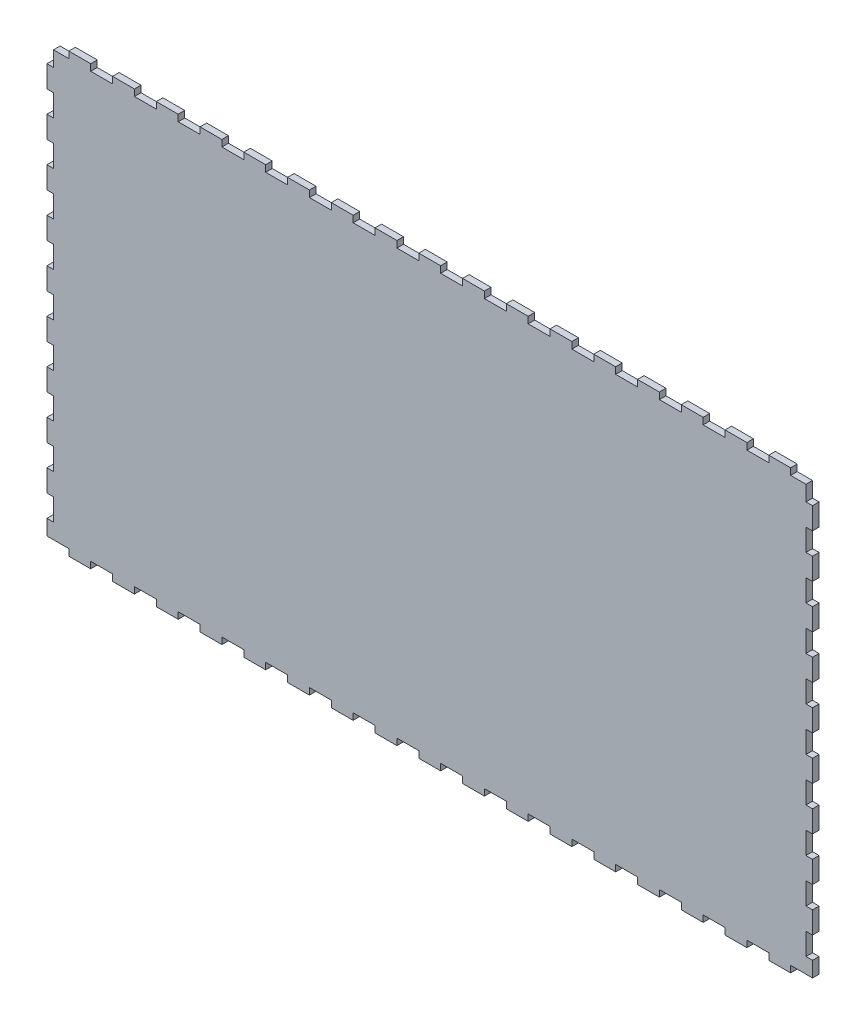
SolidWorks part; units mm, degrees
ref_plane "Alzado" through (0, 0, 0) normal (0, 0, 1) x (1, 0, 0)
ref_plane "Planta" through (0, 0, 0) normal (0, 1, 0) x (1, 0, 0)
ref_plane "Vista lateral" through (0, 0, 0) normal (1, 0, 0) x (0, 0, -1)
sketch "Croquis1" plane through (0, 0, 0) normal (0, 0, 1) x (1, 0, 0)
  line L0 (-175, -97) -> (-165, -97)
  line L1 (-155, -97) -> (-145, -97)
  line L2 (-175, 80) -> (-172, 80)
  line L3 (-172, 70) -> (-175, 70)
  line L4 (175, -100) -> (-175, 100) construction
  line L5 (175, 100) -> (-175, -100) construction
  line L102 (172, 97) -> (172, 90)
  line L103 (-172, 90) -> (-175, 90)
  line L104 (-175, 90) -> (-175, 80)
  line L105 (-175, 80) -> (-172, 80)
  line L106 (-175, 70) -> (-175, 60)
  line L107 (-175, 60) -> (-172, 60)
  line L108 (-172, 80) -> (-172, 70)
  line L109 (-175, 60) -> (-172, 60)
  line L110 (-172, 50) -> (-175, 50)
  line L111 (-175, 50) -> (-175, 40)
  line L112 (-175, 40) -> (-172, 40)
  line L113 (-172, 60) -> (-172, 50)
  line L114 (-175, 40) -> (-172, 40)
  line L115 (-172, 30) -> (-175, 30)
  line L116 (-175, 30) -> (-175, 20)
  line L117 (-175, 20) -> (-172, 20)
  line L118 (-172, 40) -> (-172, 30)
  line L119 (-175, 20) -> (-172, 20)
  line L120 (-172, 10) -> (-175, 10)
  line L121 (-175, 10) -> (-175, 0)
  line L122 (-175, 0) -> (-172, 0)
  line L123 (-172, 20) -> (-172, 10)
  line L124 (-175, 0) -> (-172, 0)
  line L125 (-172, -10) -> (-175, -10)
  line L126 (-175, -10) -> (-175, -20)
  line L127 (-175, -20) -> (-172, -20)
  line L128 (-172, 0) -> (-172, -10)
  line L129 (-175, -20) -> (-172, -20)
  line L130 (-172, -30) -> (-175, -30)
  line L131 (-175, -30) -> (-175, -40)
  line L132 (-175, -40) -> (-172, -40)
  line L133 (-172, -20) -> (-172, -30)
  line L134 (-175, -40) -> (-172, -40)
  line L135 (-172, -50) -> (-175, -50)
  line L136 (-175, -50) -> (-175, -60)
  line L137 (-175, -60) -> (-172, -60)
  line L138 (-172, -40) -> (-172, -50)
  line L139 (-175, -60) -> (-172, -60)
  line L140 (-172, -70) -> (-175, -70)
  line L141 (-175, -70) -> (-175, -80)
  line L142 (-175, -80) -> (-172, -80)
  line L143 (-172, -60) -> (-172, -70)
  line L144 (-175, -80) -> (-172, -80)
  line L145 (-172, -90) -> (-175, -90)
  line L146 (-175, -90) -> (-175, -97)
  line L147 (-145, -97) -> (-145, -100)
  line L148 (-172, -80) -> (-172, -90)
  line L149 (-33.9734, 0) -> (38.9566, 0) construction
  line L150 (172, -80) -> (172, -90)
  line L151 (165, 97) -> (172, 97)
  line L152 (175, -90) -> (175, -97)
  line L153 (172, -90) -> (175, -90)
  line L154 (175, -80) -> (172, -80)
  line L155 (172, -60) -> (172, -70)
  line L156 (175, -80) -> (172, -80)
  line L157 (175, -70) -> (175, -80)
  line L158 (172, -70) -> (175, -70)
  line L159 (175, -60) -> (172, -60)
  line L160 (172, -40) -> (172, -50)
  line L161 (175, -60) -> (172, -60)
  line L162 (175, -50) -> (175, -60)
  line L163 (172, -50) -> (175, -50)
  line L164 (175, -40) -> (172, -40)
  line L165 (172, -20) -> (172, -30)
  line L166 (175, -40) -> (172, -40)
  line L167 (175, -30) -> (175, -40)
  line L168 (172, -30) -> (175, -30)
  line L169 (175, -20) -> (172, -20)
  line L170 (172, 0) -> (172, -10)
  line L171 (175, -20) -> (172, -20)
  line L172 (175, -10) -> (175, -20)
  line L173 (172, -10) -> (175, -10)
  line L174 (175, 0) -> (172, 0)
  line L175 (172, 20) -> (172, 10)
  line L176 (175, 0) -> (172, 0)
  line L177 (175, 10) -> (175, 0)
  line L178 (172, 10) -> (175, 10)
  line L179 (175, 20) -> (172, 20)
  line L180 (172, 40) -> (172, 30)
  line L181 (175, 20) -> (172, 20)
  line L182 (175, 30) -> (175, 20)
  line L183 (172, 30) -> (175, 30)
  line L184 (175, 40) -> (172, 40)
  line L185 (172, 60) -> (172, 50)
  line L186 (175, 40) -> (172, 40)
  line L187 (175, 50) -> (175, 40)
  line L188 (172, 50) -> (175, 50)
  line L189 (175, 60) -> (172, 60)
  line L190 (172, 80) -> (172, 70)
  line L191 (175, 60) -> (172, 60)
  line L192 (175, 70) -> (175, 60)
  line L193 (175, 80) -> (172, 80)
  line L194 (175, 90) -> (175, 80)
  line L195 (172, 90) -> (175, 90)
  line L196 (172, 70) -> (175, 70)
  line L197 (175, 80) -> (172, 80)
  line L198 (-165, -97) -> (-165, -100)
  line L199 (-165, -100) -> (-155, -100)
  line L200 (-155, -100) -> (-155, -97)
  line L201 (-145, -100) -> (-135, -100)
  line L202 (-135, -100) -> (-135, -97)
  line L203 (-135, -97) -> (-125, -97)
  line L204 (-125, -97) -> (-125, -100)
  line L205 (-125, -100) -> (-115, -100)
  line L206 (-115, -100) -> (-115, -97)
  line L207 (-115, -97) -> (-105, -97)
  line L208 (-105, -97) -> (-105, -100)
  line L209 (-105, -100) -> (-95, -100)
  line L210 (-95, -100) -> (-95, -97)
  line L211 (-95, -97) -> (-85, -97)
  line L212 (-85, -97) -> (-85, -100)
  line L213 (-85, -100) -> (-75, -100)
  line L214 (-75, -100) -> (-75, -97)
  line L215 (-75, -97) -> (-65, -97)
  line L216 (-65, -97) -> (-65, -100)
  line L217 (-65, -100) -> (-55, -100)
  line L218 (-55, -100) -> (-55, -97)
  line L219 (-55, -97) -> (-45, -97)
  line L220 (-45, -97) -> (-45, -100)
  line L221 (-45, -100) -> (-35, -100)
  line L222 (-35, -100) -> (-35, -97)
  line L223 (-35, -97) -> (-25, -97)
  line L224 (-25, -97) -> (-25, -100)
  line L225 (-25, -100) -> (-15, -100)
  line L226 (-15, -100) -> (-15, -97)
  line L227 (-15, -97) -> (-5, -97)
  line L228 (-5, -97) -> (-5, -100)
  line L229 (-5, -100) -> (5, -100)
  line L230 (5, -100) -> (5, -97)
  line L231 (5, -97) -> (15, -97)
  line L232 (15, -97) -> (15, -100)
  line L233 (15, -100) -> (25, -100)
  line L234 (25, -100) -> (25, -97)
  line L235 (25, -97) -> (35, -97)
  line L236 (35, -97) -> (35, -100)
  line L237 (35, -100) -> (45, -100)
  line L238 (45, -100) -> (45, -97)
  line L239 (45, -97) -> (55, -97)
  line L240 (55, -97) -> (55, -100)
  line L241 (55, -100) -> (65, -100)
  line L242 (65, -100) -> (65, -97)
  line L243 (65, -97) -> (75, -97)
  line L244 (75, -97) -> (75, -100)
  line L245 (75, -100) -> (85, -100)
  line L246 (85, -100) -> (85, -97)
  line L247 (85, -97) -> (95, -97)
  line L248 (95, -97) -> (95, -100)
  line L249 (95, -100) -> (105, -100)
  line L250 (105, -100) -> (105, -97)
  line L251 (105, -97) -> (115, -97)
  line L252 (115, -97) -> (115, -100)
  line L253 (115, -100) -> (125, -100)
  line L254 (125, -100) -> (125, -97)
  line L255 (125, -97) -> (135, -97)
  line L256 (135, -97) -> (135, -100)
  line L257 (135, -100) -> (145, -100)
  line L258 (145, -100) -> (145, -97)
  line L259 (145, -97) -> (155, -97)
  line L260 (155, -97) -> (155, -100)
  line L261 (155, -100) -> (165, -100)
  line L262 (165, -100) -> (165, -97)
  line L263 (165, -97) -> (175, -97)
  line L264 (165, 100) -> (165, 97)
  line L265 (155, 100) -> (165, 100)
  line L266 (155, 97) -> (155, 100)
  line L267 (145, 97) -> (155, 97)
  line L268 (145, 100) -> (145, 97)
  line L269 (135, 100) -> (145, 100)
  line L270 (135, 97) -> (135, 100)
  line L271 (125, 97) -> (135, 97)
  line L272 (125, 100) -> (125, 97)
  line L273 (115, 100) -> (125, 100)
  line L274 (115, 97) -> (115, 100)
  line L275 (105, 97) -> (115, 97)
  line L276 (105, 100) -> (105, 97)
  line L277 (95, 100) -> (105, 100)
  line L278 (95, 97) -> (95, 100)
  line L279 (85, 97) -> (95, 97)
  line L280 (85, 100) -> (85, 97)
  line L281 (75, 100) -> (85, 100)
  line L282 (75, 97) -> (75, 100)
  line L283 (65, 97) -> (75, 97)
  line L284 (65, 100) -> (65, 97)
  line L285 (55, 100) -> (65, 100)
  line L286 (55, 97) -> (55, 100)
  line L287 (45, 97) -> (55, 97)
  line L288 (45, 100) -> (45, 97)
  line L289 (35, 100) -> (45, 100)
  line L290 (35, 97) -> (35, 100)
  line L291 (25, 97) -> (35, 97)
  line L292 (25, 100) -> (25, 97)
  line L293 (15, 100) -> (25, 100)
  line L294 (15, 97) -> (15, 100)
  line L295 (5, 97) -> (15, 97)
  line L296 (5, 100) -> (5, 97)
  line L297 (-5, 100) -> (5, 100)
  line L298 (-5, 97) -> (-5, 100)
  line L299 (-15, 97) -> (-5, 97)
  line L300 (-15, 100) -> (-15, 97)
  line L301 (-25, 100) -> (-15, 100)
  line L302 (-25, 97) -> (-25, 100)
  line L303 (-35, 97) -> (-25, 97)
  line L304 (-35, 100) -> (-35, 97)
  line L305 (-45, 100) -> (-35, 100)
  line L306 (-45, 97) -> (-45, 100)
  line L307 (-55, 97) -> (-45, 97)
  line L308 (-55, 100) -> (-55, 97)
  line L309 (-65, 100) -> (-55, 100)
  line L310 (-65, 97) -> (-65, 100)
  line L311 (-75, 97) -> (-65, 97)
  line L312 (-75, 100) -> (-75, 97)
  line L313 (-85, 100) -> (-75, 100)
  line L314 (-85, 97) -> (-85, 100)
  line L315 (-95, 97) -> (-85, 97)
  line L316 (-95, 100) -> (-95, 97)
  line L317 (-105, 100) -> (-95, 100)
  line L318 (-105, 97) -> (-105, 100)
  line L319 (-115, 97) -> (-105, 97)
  line L320 (-115, 100) -> (-115, 97)
  line L321 (-125, 100) -> (-115, 100)
  line L322 (-125, 97) -> (-125, 100)
  line L323 (-135, 97) -> (-125, 97)
  line L324 (-135, 100) -> (-135, 97)
  line L325 (-145, 100) -> (-135, 100)
  line L326 (-155, 100) -> (-155, 97)
  line L327 (-165, 100) -> (-155, 100)
  line L328 (-165, 97) -> (-165, 100)
  line L329 (-145, 97) -> (-145, 100)
  line L330 (-155, 97) -> (-145, 97)
  line L331 (-172, 97) -> (-165, 97)
  line L332 (-172, 97) -> (-172, 90)
  point P0 (0, 0)
  point P1 (0, 0)
extrude "Saliente-Extruir1" add sketch "Croquis1" along normal blind 3 contours L331 L332 L103 L104 L2 L108 L3 L106 L107 L113 L110 L111 L112 L118 L115 L116 L117 L123 L120 L121 L122 L128 L125 L126 L127 L133 L130 L131 L132 L138 L135 L136 L137 L143 L140 L141 L142 L148 L145 L146 L0 L198 L199 L200 L1 L147 L201 L202 L203 L204 L205
